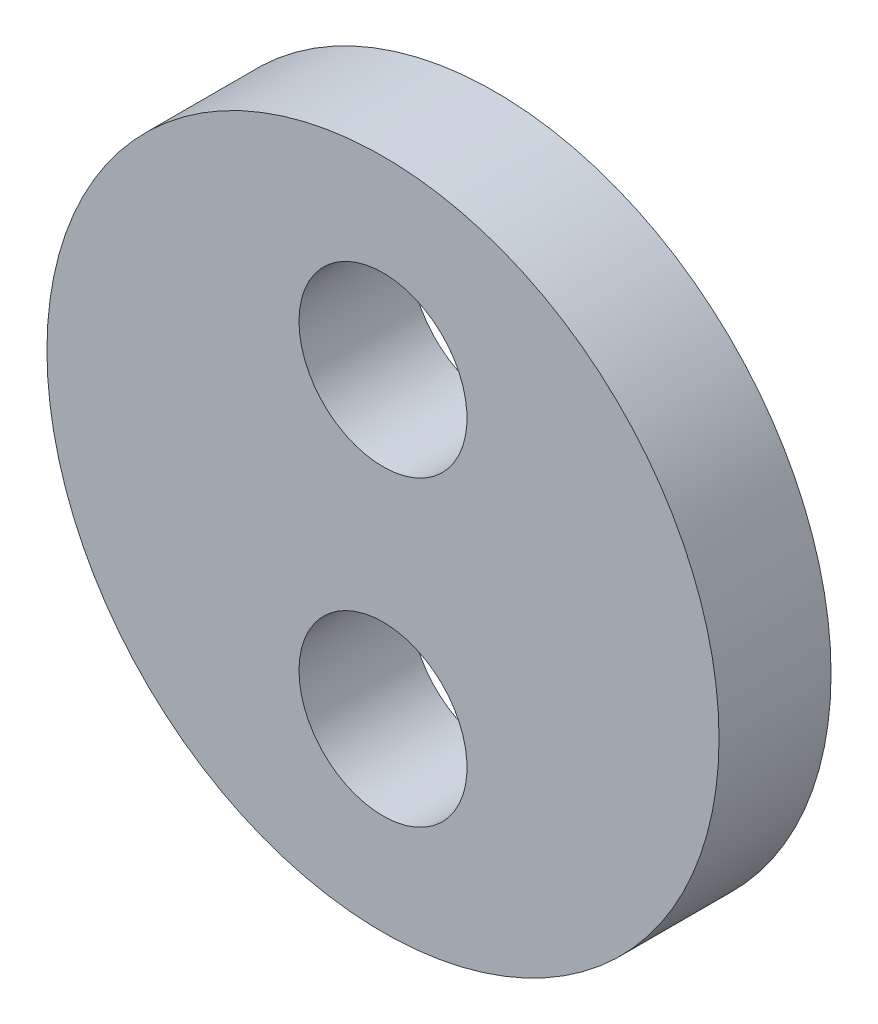
SolidWorks part; units mm, degrees
ref_plane "Front Plane" through (0, 0, 0) normal (0, 0, 1) x (1, 0, 0)
ref_plane "Top Plane" through (0, 0, 0) normal (0, 1, 0) x (1, 0, 0)
ref_plane "Right Plane" through (0, 0, 0) normal (1, 0, 0) x (0, 0, -1)
sketch "Sketch2" plane through (0, 0, 0) normal (0, 0, 1) x (1, 0, 0)
  circle A3 centre (0, 0) radius 5 construction
  circle A14 centre (0, 0) radius 6
  circle A15 centre (0, 2.7) radius 1.5
  circle A16 centre (0, -2.7) radius 1.5
  circle A19 centre (0, 0) radius 5 construction
  point P8 (0, 0)
  point P11 (0, 0)
  point P13 (0, 0)
  point P14 (0, 0)
  dimension "D2" = 2.7
  dimension "D3" = 3
  dimension "D5" = 2.7
  dimension "D1" = 1
  dimension "D4" = 2
extrude "Boss-Extrude1" add sketch "Sketch2" along normal blind 2 from surface at 0.5
ref_plane "Plane1" through (20.9, 0, 0) normal (1, 0, 0) x (0, 0, -1)
ref_plane "Plane2" through (53.5, 0, 0) normal (-1, 0, 0) x (0, 0, 1)
